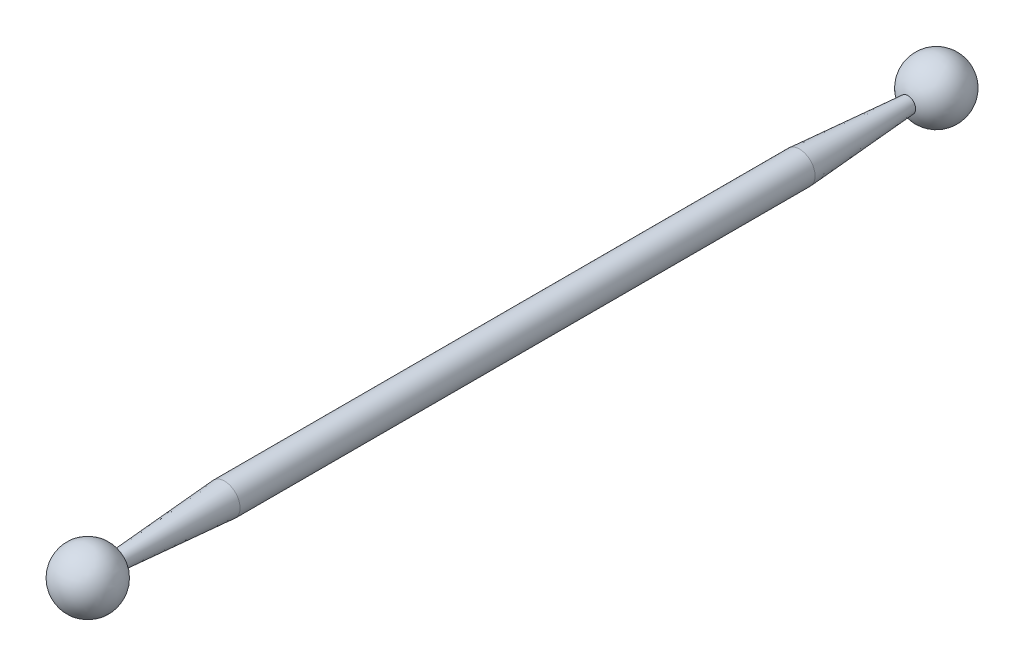
SolidWorks part; units mm, degrees
ref_plane "Front Plane" through (0, 0, 0) normal (0, 0, 1) x (1, 0, 0)
ref_plane "Top Plane" through (0, 0, 0) normal (0, 1, 0) x (1, 0, 0)
ref_plane "Right Plane" through (0, 0, 0) normal (1, 0, 0) x (0, 0, -1)
sketch "Sketch2" plane through (0, 0, 0) normal (0, 0, 1) x (1, 0, 0)
  circle A0 centre (0, 0) radius 5
  dimension "D1" = 10
ref_plane "Plane1" through (0, 0, 35) normal (0, 0, 1) x (1, 0, 0)
sketch "Sketch3" plane through (0, 0, 35) normal (0, 0, 1) x (1, 0, 0)
  circle A0 centre (0, 0) radius 2.5
  dimension "D1" = 5
loft "Loft1" add profiles "Sketch2", "Sketch3"
sketch "Sketch4" plane through (0, 0, 0) normal (0, 0, -1) x (-1, 0, 0)
  circle A0 centre (0, 0) radius 5
  dimension "D1" = 10
extrude "Boss-Extrude2" add sketch "Sketch4" along normal blind 185
ref_plane "Plane2" through (0, 0, -185) normal (0, 0, -1) x (-1, 0, 0)
sketch "Sketch5" plane through (0, 0, -185) normal (0, 0, -1) x (-1, 0, 0)
  circle A0 centre (0, 0) radius 5
  dimension "D1" = 10
ref_plane "Plane3" through (0, 0, -220) normal (0, 0, -1) x (-1, 0, 0)
sketch "Sketch6" plane through (0, 0, -220) normal (0, 0, -1) x (-1, 0, 0)
  circle A0 centre (0, 0) radius 2.5
  dimension "D1" = 5
loft "Loft2" add profiles "Sketch5", "Sketch6"
ref_plane "Plane4" through (0, 0, 44) normal (0, 0, 1) x (1, 0, 0)
sketch "Sketch8" plane through (0, 0, 44) normal (0, 0, 1) x (1, 0, 0)
  line L0 (0, 9.5) -> (0, -9.5)
  arc A0 (0, -9.5) -> (0, 9.5) centre (0, 0) ccw
  dimension "D1" = 19
revolve "Revolve1" add sketch "Sketch8" angle 360 about L0
ref_plane "Plane5" through (0, 0, -229) normal (0, 0, -1) x (-1, 0, 0)
sketch "Sketch9" plane through (0, 0, -229) normal (0, 0, -1) x (-1, 0, 0)
  line L0 (0, 9.5) -> (0, -9.5)
  arc A0 (0, -9.5) -> (0, 9.5) centre (0, 0) ccw
  dimension "D1" = 19
revolve "Revolve2" add sketch "Sketch9" angle 360 about L0
